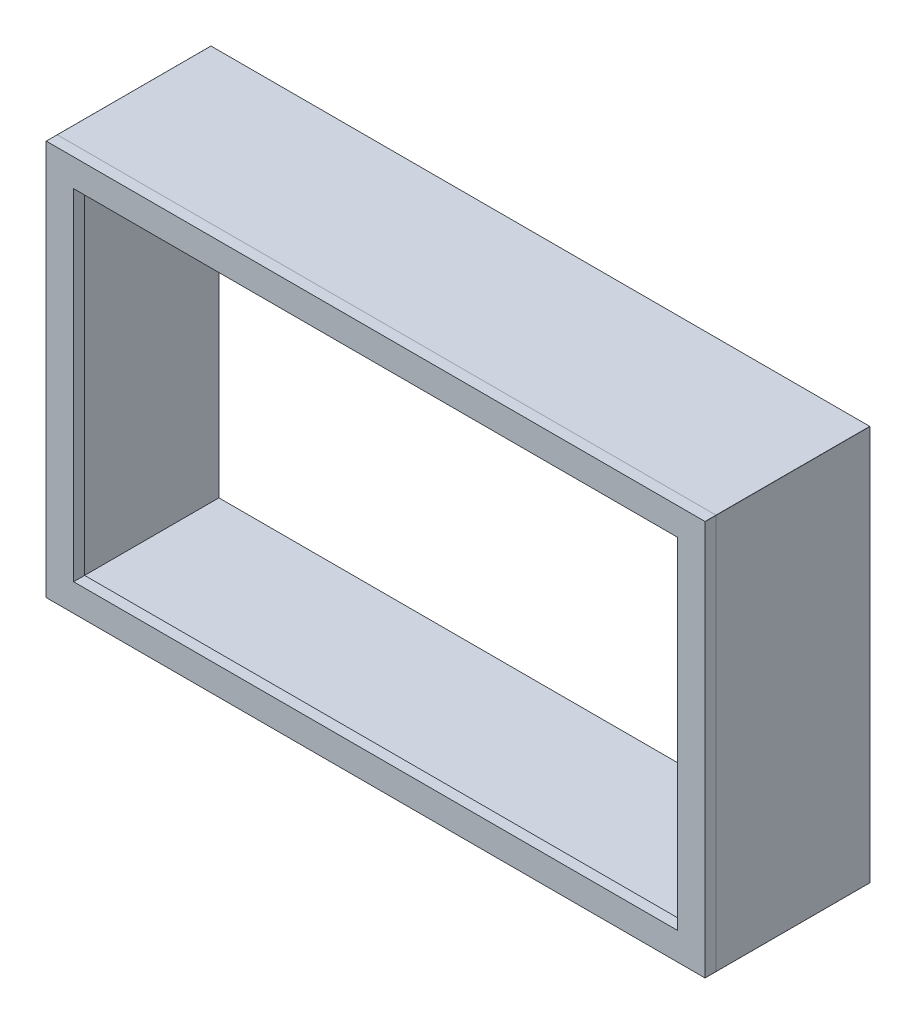
SolidWorks part; units mm, degrees
ref_plane "Front Plane" through (0, 0, 0) normal (0, 0, 1) x (1, 0, 0)
ref_plane "Top Plane" through (0, 0, 0) normal (0, 1, 0) x (1, 0, 0)
ref_plane "Right Plane" through (0, 0, 0) normal (1, 0, 0) x (0, 0, -1)
sketch "Sketch1" plane through (0, 0, 0) normal (0, 0, 1) x (1, 0, 0)
  line L1 (761.746, -457.2) -> (-761.746, -457.2)
  line L2 (762, -456.946) -> (762, 456.946)
  line L3 (761.746, 457.2) -> (-761.746, 457.2)
  line L4 (-762, -456.946) -> (-762, 456.946)
  line L5 (762, -457.2) -> (-762, 457.2) construction
  line L6 (762, 457.2) -> (-762, -457.2) construction
  arc A0 (-761.746, -457.2) -> (-762, -456.946) centre (-761.746, -456.946) cw
  arc A1 (761.746, -457.2) -> (762, -456.946) centre (761.746, -456.946) ccw
  arc A2 (762, 456.946) -> (761.746, 457.2) centre (761.746, 456.946) ccw
  arc A3 (-761.746, 457.2) -> (-762, 456.946) centre (-761.746, 456.946) ccw
  point P0 (0, 0)
  dimension "D3" = 0.254
  dimension "D1" = 1524
  dimension "D2" = 914.4
extrude "Extrude-Thin1" add sketch "Sketch1" along normal blind 203.2 and the other way blind 152.4 thin
sketch "Sketch2" plane through (0, 0, 203.2) normal (0, 0, 1) x (1, 0, 0)
  line L4 (-762, 456.946) -> (-762, -456.946)
  line L5 (-761.746, -457.2) -> (761.746, -457.2)
  line L6 (762, -456.946) -> (762, 456.946)
  line L7 (761.746, 457.2) -> (-761.746, 457.2)
  line L8 (-762, 456.946) -> (-762, -456.946)
  line L9 (-761.746, -457.2) -> (761.746, -457.2)
  line L10 (762, -456.946) -> (762, 456.946)
  line L11 (761.746, 457.2) -> (-761.746, 457.2)
  arc A4 (-762, -456.946) -> (-761.746, -457.2) centre (-761.746, -456.946) ccw
  arc A5 (-762, -456.946) -> (-761.746, -457.2) centre (-761.746, -456.946) ccw
  arc A6 (761.746, -457.2) -> (762, -456.946) centre (761.746, -456.946) ccw
  arc A7 (761.746, -457.2) -> (762, -456.946) centre (761.746, -456.946) ccw
  arc A8 (762, 456.946) -> (761.746, 457.2) centre (761.746, 456.946) ccw
  arc A9 (762, 456.946) -> (761.746, 457.2) centre (761.746, 456.946) ccw
  arc A10 (-761.746, 457.2) -> (-762, 456.946) centre (-761.746, 456.946) ccw
  arc A11 (-761.746, 457.2) -> (-762, 456.946) centre (-761.746, 456.946) ccw
  dimension "D1" = 0
extrude "Extrude-Thin2" add sketch "Sketch2" along normal blind 25.4 separate body thin
